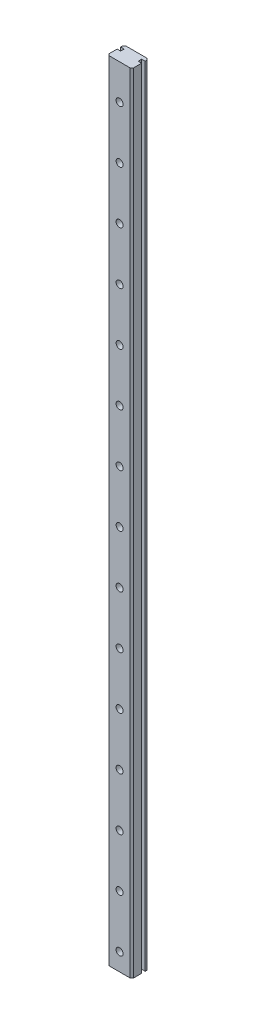
SolidWorks part; units mm, degrees
material "AISI 304"
ref_plane "前视基准面" through (0, 0, 0) normal (0, 0, 1) x (1, 0, 0)
ref_plane "上视基准面" through (0, 0, 0) normal (0, 1, 0) x (1, 0, 0)
ref_plane "右视基准面" through (0, 0, 0) normal (1, 0, 0) x (0, 0, -1)
other "Configuration Table"
sketch "草图1" plane through (0, 0, 0) normal (0, 1, 0) x (1, 0, 0)
  line L0 (0, 0) -> (0, 7.157) construction
  line L1 (-3.5, -2.4) -> (3.5, -2.4)
  line L2 (-3.5, -2.4) -> (-3.5, 2.4)
  line L3 (-3.5, 2.4) -> (3.5, 2.4)
  line L4 (3.5, -2.4) -> (3.5, 2.4)
  line L5 (-3.5, -2.4) -> (3.5, 2.4) construction
  line L6 (-3.5, 2.4) -> (3.5, -2.4) construction
  line L7 (3.5, 1.4) -> (2.5, 1.4)
  line L8 (2.5, 1.4) -> (2.5, 0.4)
  line L9 (2.5, 0.4) -> (3.5, 0.4)
  line L10 (-2.5, 0.4) -> (-3.5, 0.4)
  line L11 (-2.5, 1.4) -> (-2.5, 0.4)
  line L12 (-3.5, 1.4) -> (-2.5, 1.4)
  point P0 (0, 0)
  dimension "D1" = 7
  dimension "D2" = 4.8
  dimension "D3" = 1
  dimension "D4" = 1
  dimension "D5" = 1
extrude "凸台-拉伸1" add sketch "草图1" along normal blind 225 contours L2 L12 L11 L10 L1 L4 L9 L8 L7 L3
sketch "草图2" plane through (0, 0, -2.4) normal (0, 0, -1) x (-1, 0, 0)
  line L0 (3.5, 0) -> (-3.5, 0) construction
  line L1 (-3.5, 225) -> (-3.5, 0) construction
  circle A0 centre (0, 5) radius 1
  circle A1 centre (0, 20) radius 1
  circle A2 centre (0, 35) radius 1
  circle A3 centre (0, 50) radius 1
  circle A4 centre (0, 65) radius 1
  circle A5 centre (0, 80) radius 1
  circle A6 centre (0, 95) radius 1
  circle A7 centre (0, 110) radius 1
  circle A8 centre (0, 125) radius 1
  circle A9 centre (0, 140) radius 1
  circle A10 centre (0, 155) radius 1
  circle A11 centre (0, 170) radius 1
  circle A12 centre (0, 185) radius 1
  circle A13 centre (0, 200) radius 1
  circle A14 centre (0, 215) radius 1
  circle A15 centre (0, 230) radius 1
  dimension "D1" = 2
  dimension "D2" = 5
  dimension "D5" = 15
  dimension "D3" = 3.5
  dimension "D4" = 16
extrude "切除-拉伸1" cut sketch "草图2" against normal blind 10
chamfer "倒角1" distance 0.5 angle 45 4 edges at (-3.5, 112.5, 2.4) (3.5, 112.5, 2.4) (-3.5, 112.5, -2.4) (3.5, 112.5, -2.4)
sketch "草图3" plane through (0, 0, -2.4) normal (0, 0, -1) x (-1, 0, 0)
  circle A0 centre (0, 5) radius 2.3833
  circle A1 centre (0, 20) radius 2.3833
  circle A2 centre (0, 35) radius 2.3833
  circle A3 centre (0, 50) radius 2.3833
  circle A4 centre (0, 65) radius 2.3833
  circle A5 centre (0, 80) radius 2.3833
  circle A6 centre (0, 95) radius 2.3833
  circle A7 centre (0, 110) radius 2.3833
  circle A8 centre (0, 125) radius 2.3833
  circle A9 centre (0, 140) radius 2.3833
  circle A10 centre (0, 155) radius 2.3833
  circle A11 centre (0, 170) radius 2.3833
  circle A12 centre (0, 185) radius 2.3833
  circle A13 centre (0, 200) radius 2.3833
  circle A14 centre (0, 215) radius 2.3833
  circle A15 centre (0, 230) radius 2.3833
  dimension "D1" = 4.7666
  dimension "D3" = 15
  dimension "D2" = 16
extrude "切除-拉伸2" cut sketch "草图3" against normal blind 1
